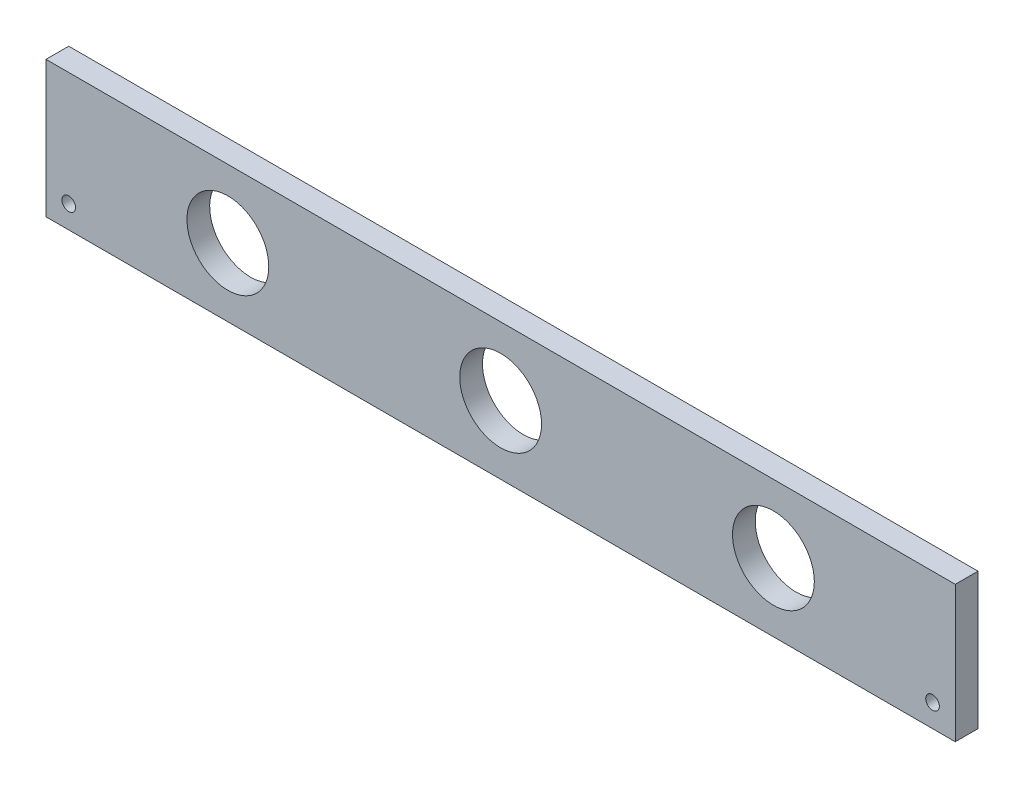
SolidWorks part; units mm, degrees
material "Perspex (TM) GS Acrylic Cast Sheet"
ref_plane "Front Plane" through (0, 0, 0) normal (0, 0, 1) x (1, 0, 0)
ref_plane "Top Plane" through (0, 0, 0) normal (0, 1, 0) x (1, 0, 0)
ref_plane "Right Plane" through (0, 0, 0) normal (1, 0, 0) x (0, 0, -1)
sketch "Sketch1" plane through (0, 0, 0) normal (1, 0, 0) x (0, 0, -1)
  line L0 (55, 0) -> (-55, 0) construction
  line L2 (5, 0) -> (0, 0)
  line L3 (5, 0) -> (5, 30)
  line L4 (5, 30) -> (0, 30)
  line L5 (0, 30) -> (0, 0)
  line L6 (0, 55) -> (0, -55) construction
  dimension "D1" = 5
  dimension "D5" = 30
extrude "Boss-Extrude1" add sketch "Sketch1" along normal mid plane 200
sketch "Sketch4" plane through (0, 0, 0) normal (0, 0, 1) x (1, 0, 0)
  line L0 (0, -55) -> (0, 55) construction
  line L1 (100, 30) -> (-100, 30) construction
  line L2 (-100, 30) -> (-100, 0) construction
  line L3 (100, 0) -> (-100, 0) construction
  line L4 (100, 30) -> (100, 0) construction
  circle A0 centre (0, 15) radius 9
  circle A1 centre (60, 15) radius 9
  circle A2 centre (-60, 15) radius 9
  circle A3 centre (-95, 5) radius 1.5
  circle A4 centre (95, 5) radius 1.5
  dimension "D1" = 18
  dimension "D2" = 60
  dimension "D3" = 60
  dimension "D4" = 15
  dimension "D5" = 3
  dimension "D6" = 5
  dimension "D7" = 5
  dimension "D8" = 5
extrude "Cut-Extrude2" cut sketch "Sketch4" against normal blind 10
